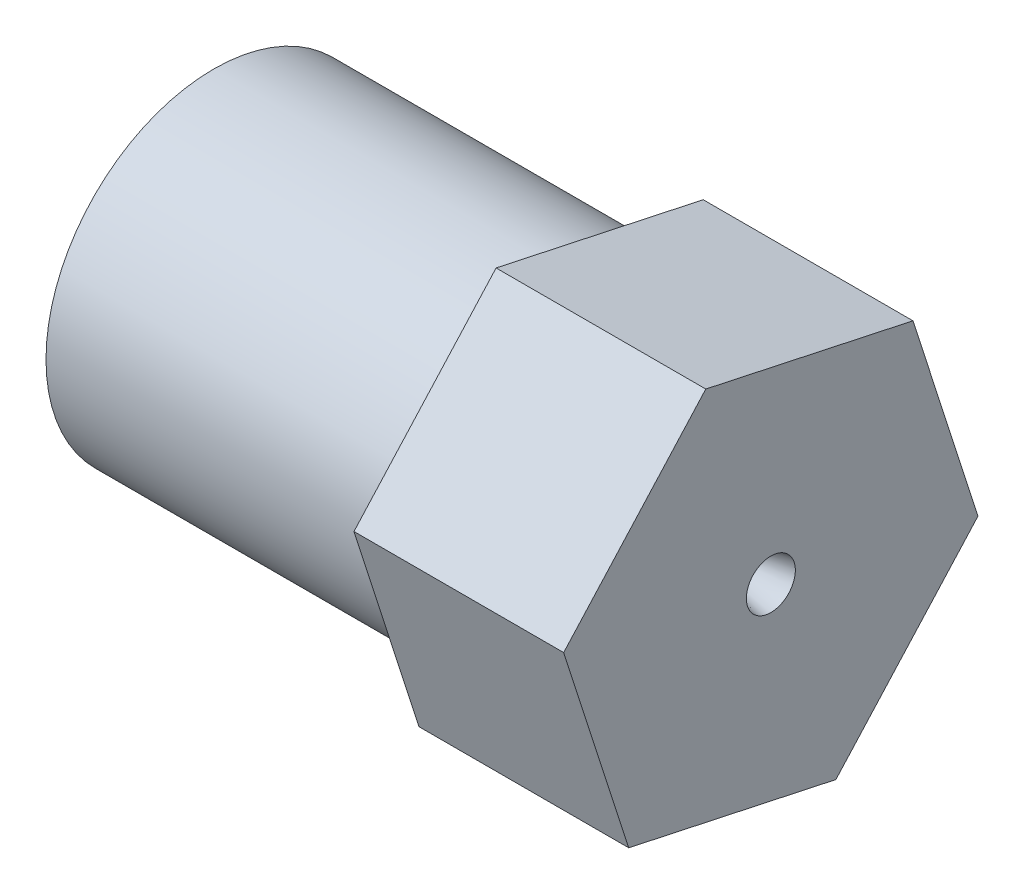
SolidWorks part; units mm, degrees
ref_plane "Front Plane" through (0, 0, 0) normal (0, 0, 1) x (1, 0, 0)
ref_plane "Top Plane" through (0, 0, 0) normal (0, 1, 0) x (1, 0, 0)
ref_plane "Right Plane" through (0, 0, 0) normal (1, 0, 0) x (0, 0, -1)
sketch "Sketch1" plane through (0, 0, 0) normal (0, 0, 1) x (1, 0, 0)
  line L0 (0, 0) -> (1.9874, 0) construction
  line L1 (0.1368, 1.0241) -> (1.9874, 1.6977) construction
  line L2 (-1.0607, 1.4393) -> (-3.1364, 3.5151)
  line L3 (-31.75, 4.445) -> (-31.75, 10.16) construction
  line L4 (-5.3814, 4.445) -> (-31.75, 4.445) construction
  line L5 (-31.75, 10.16) -> (-10.7126, 10.16)
  line L6 (1.9874, 10.16) -> (1.9874, 1.4832)
  line L7 (1.9874, 1.4832) -> (13.1512, 3.0522) construction
  line L8 (-10.7126, 10.16) -> (1.9874, 10.16)
  line L9 (-5.3814, 4.445) -> (-13.462, 4.445)
  line L10 (-19.939, 5.461) -> (-19.939, 6.8199)
  line L11 (-20.066, 6.9469) -> (-24.892, 6.9469)
  line L12 (-24.892, 6.9469) -> (-24.892, 7.8994)
  line L13 (-25.019, 8.0264) -> (-31.115, 8.0264)
  line L14 (-31.75, 10.16) -> (-31.75, 8.6614)
  line L15 (0, 0) -> (-31.75, 0) construction
  line L16 (-13.462, 4.445) -> (-13.462, 4.699)
  line L17 (-13.589, 4.826) -> (-19.304, 4.826)
  arc A0 (-1.0607, 1.4393) -> (0, 1) centre (0, 2.5) ccw
  arc A1 (0, 1) -> (0.1368, 1.0241) centre (0, 1.4) ccw
  arc A2 (-3.1364, 3.5151) -> (-5.3814, 4.445) centre (-5.3814, 1.27) ccw
  arc A3 (-31.115, 8.0264) -> (-31.75, 8.6614) centre (-31.115, 8.6614) cw
  arc A4 (-19.304, 4.826) -> (-19.939, 5.461) centre (-19.304, 5.461) cw
  arc A5 (-13.462, 4.699) -> (-13.589, 4.826) centre (-13.589, 4.699) ccw
  arc A6 (-19.939, 6.8199) -> (-20.066, 6.9469) centre (-20.066, 6.8199) ccw
  arc A7 (-24.892, 7.8994) -> (-25.019, 8.0264) centre (-25.019, 7.8994) ccw
  parabola Q0 (1.9874, 1.4832) -> (0.1368, 1.0241) focus (1.6622, -3.1669) apex (0.1368, 1.0241)
  point P30 (-31.75, 8.0264)
  point P39 (-24.892, 8.0264)
  dimension "D3" = 1.5
  dimension "D4" = 0.4
  dimension "D11" = 3.175
  dimension "D12" = 8
  dimension "D14" = 6.9469
  dimension "D20" = 0.635
  dimension "D21" = 0.127
  dimension "D2" = 1.9874
  dimension "D5" = 1.4832
  dimension "D6" = 20
  dimension "D7" = 45
  dimension "D8" = 8.0264
  dimension "D9" = 31.75
  dimension "D10" = 10.16
  dimension "D13" = 12.7
  dimension "D15" = 4.445
  dimension "D16" = 6.858
  dimension "D17" = 11.811
  dimension "D18" = 18.288
  dimension "D19" = 4.826
  dimension "D22" = 1
revolve "Revolve1" add sketch "Sketch1" angle 360 about L0
sketch "Sketch4" plane through (1.9874, 0, 0) normal (1, 0, 0) x (0, 0, -1)
  line L1 (3.9404, -12.2116) -> (12.5458, -2.6933)
  line L2 (12.5458, -2.6933) -> (8.6054, 9.5183)
  line L3 (8.6054, 9.5183) -> (-3.9404, 12.2116)
  line L4 (-3.9404, 12.2116) -> (-12.5458, 2.6933)
  line L5 (-12.5458, 2.6933) -> (-8.6054, -9.5183)
  line L6 (-8.6054, -9.5183) -> (3.9404, -12.2116)
  circle A0 centre (0, 0) radius 10.16
  circle A1 centre (0, 0) radius 10.16 construction
  circle A2 centre (0, 0) radius 11.1125 construction
  circle M1 centre (0, 0) radius 10.16
  dimension "D1" = 22.225
extrude "Boss-Extrude1" add sketch "Sketch4" against normal blind 12.7 contours L4 L5 M1 | L3 L4 M1 | L2 L3 M1 | L1 L2 M1 | L6 L1 M1 | L5 L6 M1
fillet "Fillet1" radius 0.635 1 edges at (-10.7126, 0, -10.16)
equation "\"D3@Sketch1\"=1.5 * \"D22@Sketch1\""
equation "\"D4@Sketch1\"=.4 * \"D22@Sketch1\""
equation "\"D5@Sketch1\"=\"D22@Sketch1\" * ( \"er\") ^ .5"
equation "\"er\" = 2.2"
